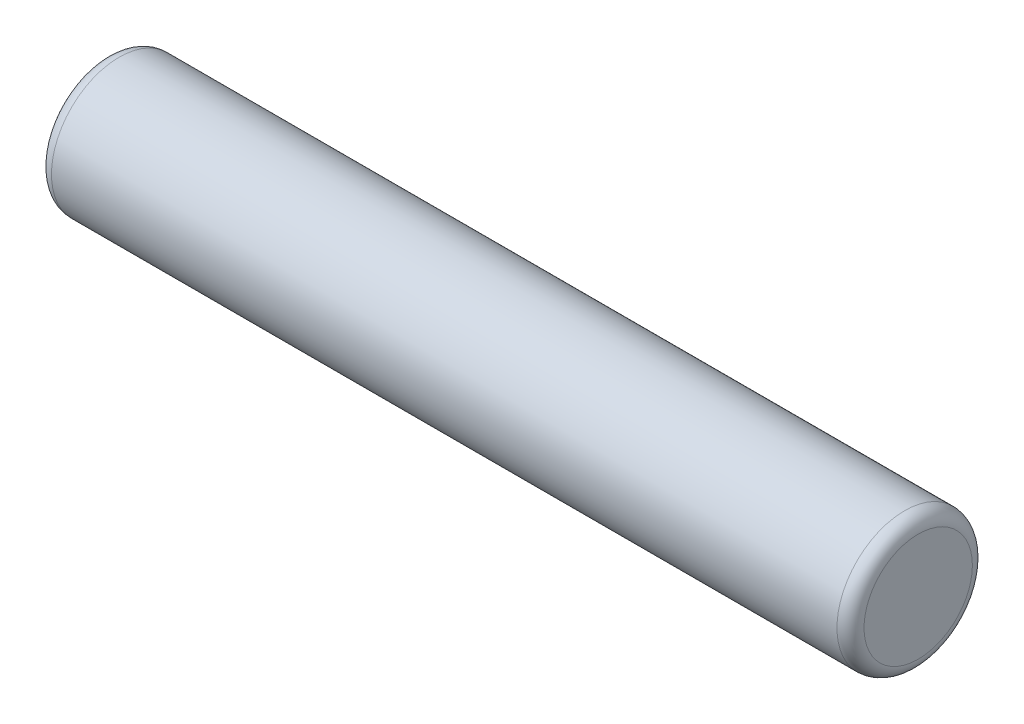
SolidWorks part; units mm, degrees
ref_plane "Vorne" through (0, 0, 0) normal (0, 0, 1) x (1, 0, 0)
ref_plane "Oben" through (0, 0, 0) normal (0, 1, 0) x (1, 0, 0)
ref_plane "Rechts" through (0, 0, 0) normal (1, 0, 0) x (0, 0, -1)
ref_plane "E_Boden" through (0, 1, 0) normal (0, 1, 0) x (1, 0, 0)
sketch "Skizze1" plane through (0, 0, 0) normal (1, 0, 0) x (0, 0, -1)
  circle A0 centre (0, 0) radius 5
  dimension "D1" = 10
extrude "Aufsatz-Linear austragen1" add sketch "Skizze1" along normal blind 60
fillet "Verrundung3" radius 1 2 edges at (0, 0, -5) (60, 0, -5)
